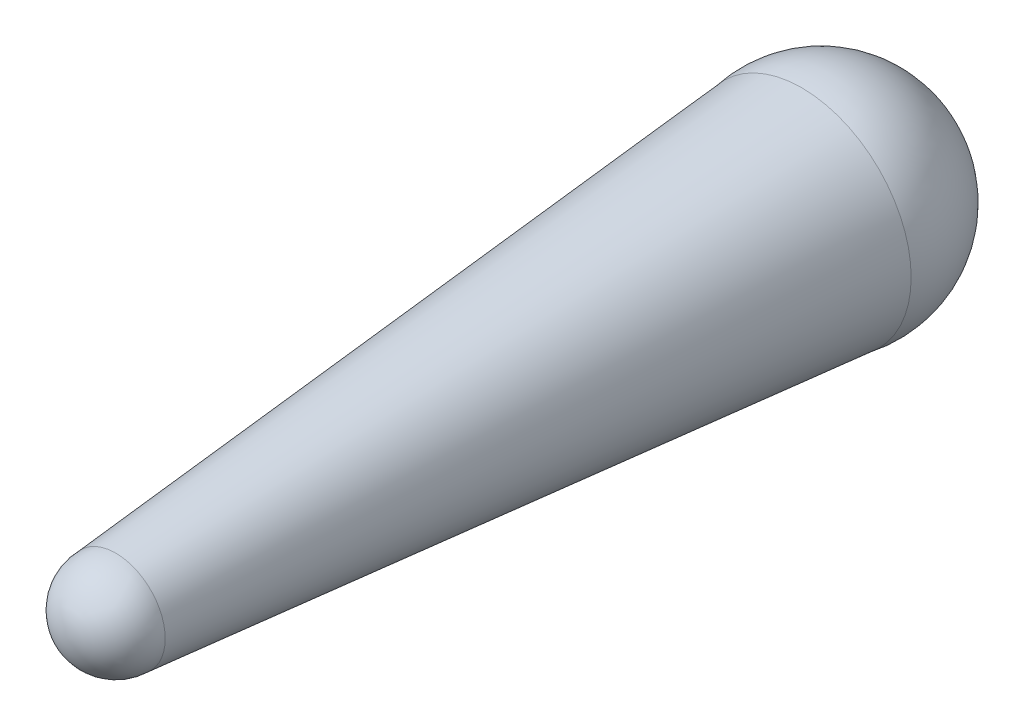
SolidWorks part; units mm, degrees
ref_plane "Front Plane" through (0, 0, 0) normal (0, 0, 1) x (1, 0, 0)
ref_plane "Top Plane" through (0, 0, 0) normal (0, 1, 0) x (1, 0, 0)
ref_plane "Right Plane" through (0, 0, 0) normal (1, 0, 0) x (0, 0, -1)
sketch "Sketch1" plane through (0, 0, 0) normal (0, 0, 1) x (1, 0, 0)
  line L0 (0, 1.575) -> (0, -1.575) construction
  line L1 (0, 1.575) -> (0, -1.575)
  arc A0 (0, -1.575) -> (0, 1.575) centre (0, 0) ccw
  dimension "D1" = 3.15
revolve "Revolve1" add sketch "Sketch1" angle 360 about L0
sketch "Sketch2" plane through (0, 0, 0) normal (0, 0, 1) x (1, 0, 0)
  circle A0 centre (0, 0) radius 1.575
  circle A1 centre (0, 0) radius 1.575 construction
extrude "Boss-Extrude1" add sketch "Sketch2" along normal blind 10 draft 5
sketch "Sketch3" plane through (0, 0, 10) normal (0, 0, 1) x (1, 0, 0)
  line L0 (0, 0.7001) -> (0, -0.7001) construction
  line L1 (0, 0.7001) -> (0, -0.7001)
  arc A0 (0, -0.7001) -> (0, 0.7001) centre (0, 0) ccw
  circle A1 centre (0, 0) radius 0.7001 construction
revolve "Revolve2" add sketch "Sketch3" angle 360 about L0
